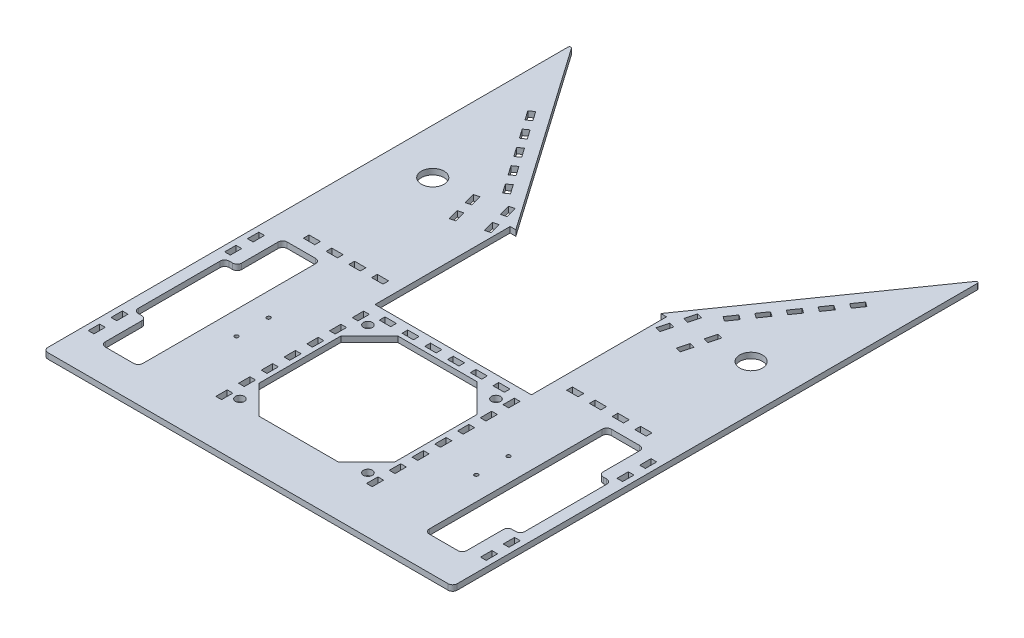
SolidWorks part; units mm, degrees
material "Acrylic (Medium-high impact)"
ref_plane "Front Plane" through (0, 0, 0) normal (0, 0, 1) x (1, 0, 0)
ref_plane "Top Plane" through (0, 0, 0) normal (0, 1, 0) x (1, 0, 0)
ref_plane "Right Plane" through (0, 0, 0) normal (1, 0, 0) x (0, 0, -1)
sketch "Sketch1" plane through (0, 0, 0) normal (0, 1, 0) x (1, 0, 0)
  line L0 (0, 0) -> (0, 279.4)
  line L1 (0, 0) -> (228.6, 0) construction
  line L2 (228.6, 0) -> (228.6, 279.4)
  line L3 (228.6, 279.4) -> (157.975, 178.425)
  line L4 (157.975, 178.425) -> (157.975, 98.425) construction
  line L5 (157.975, 98.425) -> (70.625, 98.425)
  line L6 (70.625, 98.425) -> (70.625, 178.425) construction
  line L7 (70.625, 178.425) -> (0, 279.4)
  line L8 (70.625, 178.425) -> (0, 178.425) construction
  line L9 (157.975, 178.425) -> (228.6, 178.425) construction
  line L10 (70.625, 50.8) -> (157.975, 50.8) construction
  line L11 (114.3, -1000) -> (114.3, 49000) construction
  line L12 (194.31, 2.54) -> (215.265, 2.54)
  line L13 (194.31, 2.54) -> (194.31, 104.14)
  line L14 (194.31, 104.14) -> (215.265, 104.14)
  line L15 (222.25, 27.94) -> (222.25, 78.74)
  line L16 (34.29, 53.34) -> (6.35, 53.34) construction
  line L17 (13.335, 104.14) -> (13.335, 78.74)
  line L18 (13.335, 78.74) -> (6.35, 78.74)
  line L19 (13.335, 27.94) -> (6.35, 27.94)
  line L20 (154.8, 85.725) -> (154.8, 92.075)
  line L21 (70.625, 53.975) -> (73.8, 53.975)
  line L22 (70.625, 53.975) -> (70.625, 47.625)
  line L23 (70.625, 47.625) -> (73.8, 47.625)
  line L24 (73.8, 53.975) -> (73.8, 47.625)
  line L25 (70.625, 41.275) -> (73.8, 41.275)
  line L26 (70.625, 41.275) -> (70.625, 34.925)
  line L27 (70.625, 34.925) -> (73.8, 34.925)
  line L28 (73.8, 41.275) -> (73.8, 34.925)
  line L29 (70.625, 28.575) -> (73.8, 28.575)
  line L30 (70.625, 28.575) -> (70.625, 22.225)
  line L31 (70.625, 22.225) -> (73.8, 22.225)
  line L32 (73.8, 28.575) -> (73.8, 22.225)
  line L33 (70.625, 15.875) -> (73.8, 15.875)
  line L34 (70.625, 15.875) -> (70.625, 9.525)
  line L35 (70.625, 9.525) -> (73.8, 9.525)
  line L36 (73.8, 15.875) -> (73.8, 9.525)
  line L37 (70.625, 60.325) -> (73.8, 60.325)
  line L38 (70.625, 60.325) -> (70.625, 66.675)
  line L39 (70.625, 66.675) -> (73.8, 66.675)
  line L40 (73.8, 60.325) -> (73.8, 66.675)
  line L41 (70.625, 73.025) -> (73.8, 73.025)
  line L42 (70.625, 73.025) -> (70.625, 79.375)
  line L43 (70.625, 79.375) -> (73.8, 79.375)
  line L44 (73.8, 73.025) -> (73.8, 79.375)
  line L45 (70.625, 85.725) -> (73.8, 85.725)
  line L46 (70.625, 85.725) -> (70.625, 92.075)
  line L47 (70.625, 92.075) -> (73.8, 92.075)
  line L48 (73.8, 85.725) -> (73.8, 92.075)
  line L49 (157.975, 92.075) -> (154.8, 92.075)
  line L50 (157.975, 85.725) -> (157.975, 92.075)
  line L51 (157.975, 85.725) -> (154.8, 85.725)
  line L52 (154.8, 73.025) -> (154.8, 79.375)
  line L53 (157.975, 79.375) -> (154.8, 79.375)
  line L54 (157.975, 73.025) -> (157.975, 79.375)
  line L55 (157.975, 73.025) -> (154.8, 73.025)
  line L56 (154.8, 60.325) -> (154.8, 66.675)
  line L57 (157.975, 66.675) -> (154.8, 66.675)
  line L58 (157.975, 60.325) -> (157.975, 66.675)
  line L59 (157.975, 60.325) -> (154.8, 60.325)
  line L60 (154.8, 15.875) -> (154.8, 9.525)
  line L61 (157.975, 9.525) -> (154.8, 9.525)
  line L62 (157.975, 15.875) -> (157.975, 9.525)
  line L63 (157.975, 15.875) -> (154.8, 15.875)
  line L64 (154.8, 28.575) -> (154.8, 22.225)
  line L65 (157.975, 22.225) -> (154.8, 22.225)
  line L66 (157.975, 28.575) -> (157.975, 22.225)
  line L67 (157.975, 28.575) -> (154.8, 28.575)
  line L68 (154.8, 41.275) -> (154.8, 34.925)
  line L69 (157.975, 34.925) -> (154.8, 34.925)
  line L70 (157.975, 41.275) -> (157.975, 34.925)
  line L71 (157.975, 41.275) -> (154.8, 41.275)
  line L72 (154.8, 53.975) -> (154.8, 47.625)
  line L73 (157.975, 47.625) -> (154.8, 47.625)
  line L74 (157.975, 53.975) -> (157.975, 47.625)
  line L75 (157.975, 53.975) -> (154.8, 53.975)
  line L76 (92.075, 9.525) -> (98.425, 9.525) construction
  line L77 (79.375, 9.525) -> (85.725, 9.525) construction
  line L78 (79.375, 9.525) -> (79.375, 6.35) construction
  line L79 (79.375, 6.35) -> (85.725, 6.35) construction
  line L80 (85.725, 9.525) -> (85.725, 6.35) construction
  line L81 (92.075, 9.525) -> (92.075, 6.35) construction
  line L82 (92.075, 6.35) -> (98.425, 6.35) construction
  line L83 (98.425, 9.525) -> (98.425, 6.35) construction
  line L84 (104.775, 9.525) -> (111.125, 9.525) construction
  line L85 (104.775, 9.525) -> (104.775, 6.35) construction
  line L86 (104.775, 6.35) -> (111.125, 6.35) construction
  line L87 (111.125, 9.525) -> (111.125, 6.35) construction
  line L88 (117.475, 9.525) -> (117.475, 6.35) construction
  line L89 (123.825, 6.35) -> (117.475, 6.35) construction
  line L90 (123.825, 9.525) -> (123.825, 6.35) construction
  line L91 (123.825, 9.525) -> (117.475, 9.525) construction
  line L92 (130.175, 9.525) -> (130.175, 6.35) construction
  line L93 (136.525, 6.35) -> (130.175, 6.35) construction
  line L94 (136.525, 9.525) -> (136.525, 6.35) construction
  line L95 (142.875, 9.525) -> (142.875, 6.35) construction
  line L96 (149.225, 6.35) -> (142.875, 6.35) construction
  line L97 (149.225, 9.525) -> (149.225, 6.35) construction
  line L98 (149.225, 9.525) -> (142.875, 9.525) construction
  line L99 (136.525, 9.525) -> (130.175, 9.525) construction
  line L100 (136.525, 92.075) -> (130.175, 92.075)
  line L101 (149.225, 92.075) -> (142.875, 92.075)
  line L102 (149.225, 92.075) -> (149.225, 95.25)
  line L103 (149.225, 95.25) -> (142.875, 95.25)
  line L104 (142.875, 92.075) -> (142.875, 95.25)
  line L105 (136.525, 92.075) -> (136.525, 95.25)
  line L106 (136.525, 95.25) -> (130.175, 95.25)
  line L107 (130.175, 92.075) -> (130.175, 95.25)
  line L108 (123.825, 92.075) -> (117.475, 92.075)
  line L109 (123.825, 92.075) -> (123.825, 95.25)
  line L110 (123.825, 95.25) -> (117.475, 95.25)
  line L111 (117.475, 92.075) -> (117.475, 95.25)
  line L112 (111.125, 92.075) -> (111.125, 95.25)
  line L113 (104.775, 95.25) -> (111.125, 95.25)
  line L114 (104.775, 92.075) -> (104.775, 95.25)
  line L115 (104.775, 92.075) -> (111.125, 92.075)
  line L116 (98.425, 92.075) -> (98.425, 95.25)
  line L117 (92.075, 95.25) -> (98.425, 95.25)
  line L118 (92.075, 92.075) -> (92.075, 95.25)
  line L119 (85.725, 92.075) -> (85.725, 95.25)
  line L120 (79.375, 95.25) -> (85.725, 95.25)
  line L121 (79.375, 92.075) -> (79.375, 95.25)
  line L122 (79.375, 92.075) -> (85.725, 92.075)
  line L123 (92.075, 92.075) -> (98.425, 92.075)
  line L124 (194.31, 53.34) -> (222.25, 53.34) construction
  line L125 (215.265, 2.54) -> (215.265, 27.94)
  line L126 (215.265, 27.94) -> (222.25, 27.94)
  line L127 (215.265, 78.74) -> (222.25, 78.74)
  line L128 (215.265, 104.14) -> (215.265, 78.74)
  line L129 (13.335, 2.54) -> (13.335, 27.94)
  line L130 (6.35, 27.94) -> (6.35, 78.74)
  line L131 (34.29, 104.14) -> (13.335, 104.14)
  line L132 (34.29, 2.54) -> (34.29, 104.14)
  line L133 (34.29, 2.54) -> (13.335, 2.54)
  line L134 (225.425, 94.615) -> (225.425, 100.965)
  line L135 (222.25, 24.765) -> (225.425, 24.765)
  line L136 (222.25, 24.765) -> (222.25, 18.415)
  line L137 (222.25, 18.415) -> (225.425, 18.415)
  line L138 (225.425, 24.765) -> (225.425, 18.415)
  line L139 (222.25, 12.065) -> (225.425, 12.065)
  line L140 (222.25, 12.065) -> (222.25, 5.715)
  line L141 (222.25, 5.715) -> (225.425, 5.715)
  line L142 (225.425, 12.065) -> (225.425, 5.715)
  line L143 (222.25, 100.965) -> (225.425, 100.965)
  line L144 (222.25, 94.615) -> (222.25, 100.965)
  line L145 (222.25, 94.615) -> (225.425, 94.615)
  line L146 (225.425, 81.915) -> (225.425, 88.265)
  line L147 (222.25, 88.265) -> (225.425, 88.265)
  line L148 (222.25, 81.915) -> (222.25, 88.265)
  line L149 (222.25, 81.915) -> (225.425, 81.915)
  line L150 (6.35, 81.915) -> (3.175, 81.915)
  line L151 (6.35, 81.915) -> (6.35, 88.265)
  line L152 (6.35, 88.265) -> (3.175, 88.265)
  line L153 (3.175, 81.915) -> (3.175, 88.265)
  line L154 (6.35, 94.615) -> (3.175, 94.615)
  line L155 (6.35, 94.615) -> (6.35, 100.965)
  line L156 (6.35, 100.965) -> (3.175, 100.965)
  line L157 (3.175, 94.615) -> (3.175, 100.965)
  line L158 (3.175, 12.065) -> (3.175, 5.715)
  line L159 (6.35, 5.715) -> (3.175, 5.715)
  line L160 (6.35, 12.065) -> (6.35, 5.715)
  line L161 (6.35, 12.065) -> (3.175, 12.065)
  line L162 (3.175, 24.765) -> (3.175, 18.415)
  line L163 (6.35, 18.415) -> (3.175, 18.415)
  line L164 (6.35, 24.765) -> (6.35, 18.415)
  line L165 (6.35, 24.765) -> (3.175, 24.765)
  line L166 (173.659, 189.7697) -> (177.2985, 194.9733)
  line L167 (173.659, 189.7697) -> (176.2607, 187.95)
  line L168 (178.9875, 197.6665) -> (181.5892, 195.8467) construction
  line L169 (176.2607, 187.95) -> (179.9002, 193.1535)
  line L170 (177.2985, 194.9733) -> (179.9002, 193.1535)
  line L171 (180.9379, 200.1768) -> (183.5397, 198.357)
  line L172 (187.1792, 203.5605) -> (183.5397, 198.357)
  line L173 (184.5774, 205.3803) -> (187.1792, 203.5605)
  line L174 (184.5774, 205.3803) -> (180.9379, 200.1768)
  line L175 (182.627, 202.87) -> (185.2287, 201.0502) construction
  line L176 (186.2665, 208.0735) -> (188.8682, 206.2537) construction
  line L177 (29.4646, 226.1943) -> (33.1041, 220.9908)
  line L178 (188.2169, 210.5838) -> (191.8564, 215.7873)
  line L179 (188.2169, 210.5838) -> (190.8187, 208.7641)
  line L180 (190.8187, 208.7641) -> (194.4582, 213.9676)
  line L181 (191.8564, 215.7873) -> (194.4582, 213.9676)
  line L182 (195.4959, 220.9908) -> (198.0977, 219.1711)
  line L183 (201.7372, 224.3746) -> (198.0977, 219.1711)
  line L184 (199.1354, 226.1943) -> (201.7372, 224.3746)
  line L185 (199.1354, 226.1943) -> (195.4959, 220.9908)
  line L186 (29.4646, 226.1943) -> (26.8628, 224.3746)
  line L187 (26.8628, 224.3746) -> (30.5023, 219.1711)
  line L188 (33.1041, 220.9908) -> (30.5023, 219.1711)
  line L189 (36.7436, 215.7873) -> (34.1418, 213.9676)
  line L190 (37.7813, 208.7641) -> (34.1418, 213.9676)
  line L191 (40.3831, 210.5838) -> (37.7813, 208.7641)
  line L192 (40.3831, 210.5838) -> (36.7436, 215.7873)
  line L193 (47.6621, 200.1768) -> (45.0603, 198.357)
  line L194 (44.0226, 205.3803) -> (47.6621, 200.1768)
  line L195 (44.0226, 205.3803) -> (41.4208, 203.5605)
  line L196 (41.4208, 203.5605) -> (45.0603, 198.357)
  line L197 (51.3015, 194.9733) -> (48.6998, 193.1535)
  line L198 (52.3393, 187.95) -> (48.6998, 193.1535)
  line L199 (54.941, 189.7697) -> (52.3393, 187.95)
  line L200 (54.941, 189.7697) -> (51.3015, 194.9733)
  line L201 (197.1849, 223.684) -> (199.7867, 221.8643) construction
  line L202 (202.7749, 231.3979) -> (205.3767, 229.5781)
  line L203 (209.0162, 234.7816) -> (205.3767, 229.5781)
  line L204 (206.4144, 236.6014) -> (202.7749, 231.3979)
  line L205 (206.4144, 236.6014) -> (209.0162, 234.7816)
  line L206 (22.1856, 236.6014) -> (19.5838, 234.7816)
  line L207 (22.1856, 236.6014) -> (25.8251, 231.3979)
  line L208 (19.5838, 234.7816) -> (23.2233, 229.5781)
  line L209 (25.8251, 231.3979) -> (23.2233, 229.5781)
  line L210 (76.3, 73.6934) -> (76.3, 27.9066)
  line L211 (76.3, 73.6934) -> (92.1816, 89.575)
  line L212 (92.1816, 89.575) -> (136.4184, 89.575)
  line L213 (92.1816, 12.025) -> (136.4184, 12.025)
  line L214 (76.3, 27.9066) -> (92.1816, 12.025)
  line L215 (152.3, 73.6934) -> (136.4184, 89.575)
  line L216 (152.3, 73.6934) -> (152.3, 27.9066)
  line L217 (152.3, 27.9066) -> (136.4184, 12.025)
  line L218 (165.2868, 183.9813) -> (163.6433, 177.8476)
  line L219 (165.2868, 183.9813) -> (168.1818, 183.2055)
  line L220 (163.6433, 177.8476) -> (166.5383, 177.0719)
  line L221 (168.1818, 183.2055) -> (166.5383, 177.0719)
  line L222 (180.7926, 179.8265) -> (179.1491, 173.6929)
  line L223 (180.7926, 179.8265) -> (183.6876, 179.0507)
  line L224 (179.1491, 173.6929) -> (182.0441, 172.9171)
  line L225 (183.6876, 179.0507) -> (182.0441, 172.9171)
  line L226 (161.9998, 171.714) -> (160.3563, 165.5804)
  line L227 (161.9998, 171.714) -> (164.8948, 170.9383)
  line L228 (160.3563, 165.5804) -> (163.2513, 164.8046)
  line L229 (164.8948, 170.9383) -> (163.2513, 164.8046)
  line L230 (177.5056, 167.5592) -> (175.8621, 161.4256)
  line L231 (177.5056, 167.5592) -> (180.4006, 166.7835)
  line L232 (175.8621, 161.4256) -> (178.7571, 160.6499)
  line L233 (180.4006, 166.7835) -> (178.7571, 160.6499)
  line L234 (48.1994, 166.7835) -> (49.8429, 160.6499)
  line L235 (52.7379, 161.4256) -> (49.8429, 160.6499)
  line L236 (51.0944, 167.5592) -> (48.1994, 166.7835)
  line L237 (51.0944, 167.5592) -> (52.7379, 161.4256)
  line L238 (63.7052, 170.9383) -> (65.3487, 164.8046)
  line L239 (68.2437, 165.5804) -> (65.3487, 164.8046)
  line L240 (66.6002, 171.714) -> (63.7052, 170.9383)
  line L241 (66.6002, 171.714) -> (68.2437, 165.5804)
  line L242 (44.9124, 179.0507) -> (46.5559, 172.9171)
  line L243 (49.4509, 173.6929) -> (46.5559, 172.9171)
  line L244 (47.8074, 179.8265) -> (44.9124, 179.0507)
  line L245 (47.8074, 179.8265) -> (49.4509, 173.6929)
  line L246 (60.4182, 183.2055) -> (62.0617, 177.0719)
  line L247 (64.9567, 177.8476) -> (62.0617, 177.0719)
  line L248 (63.3132, 183.9812) -> (60.4182, 183.2055)
  line L249 (63.3132, 183.9812) -> (64.9567, 177.8476)
  line L250 (43.955, 110.49) -> (50.305, 110.49)
  line L251 (56.655, 113.665) -> (63.005, 113.665)
  line L252 (56.655, 113.665) -> (56.655, 110.49)
  line L253 (56.655, 110.49) -> (63.005, 110.49)
  line L254 (63.005, 113.665) -> (63.005, 110.49)
  line L255 (50.305, 113.665) -> (50.305, 110.49)
  line L256 (43.955, 113.665) -> (50.305, 113.665)
  line L257 (43.955, 113.665) -> (43.955, 110.49)
  line L258 (31.255, 110.49) -> (37.605, 110.49)
  line L259 (37.605, 113.665) -> (37.605, 110.49)
  line L260 (31.255, 113.665) -> (37.605, 113.665)
  line L261 (31.255, 113.665) -> (31.255, 110.49)
  line L262 (18.555, 110.49) -> (24.905, 110.49)
  line L263 (24.905, 113.665) -> (24.905, 110.49)
  line L264 (18.555, 113.665) -> (24.905, 113.665)
  line L265 (18.555, 113.665) -> (18.555, 110.49)
  line L266 (0, 0) -> (0, -16.1925)
  line L267 (0, -16.1925) -> (228.6, -16.1925)
  line L268 (228.6, -16.1925) -> (228.6, 0)
  line L269 (70.625, 178.425) -> (73.8, 173.8856)
  line L270 (73.8, 173.8856) -> (70.625, 173.8856)
  line L271 (70.625, 173.8856) -> (70.625, 98.425)
  line L272 (157.975, 178.425) -> (154.8, 173.8856)
  line L273 (154.8, 173.8856) -> (157.975, 173.8856)
  line L274 (210.045, 113.665) -> (210.045, 110.49)
  line L275 (210.045, 113.665) -> (203.695, 113.665)
  line L276 (203.695, 113.665) -> (203.695, 110.49)
  line L277 (210.045, 110.49) -> (203.695, 110.49)
  line L278 (197.345, 113.665) -> (197.345, 110.49)
  line L279 (197.345, 113.665) -> (190.995, 113.665)
  line L280 (190.995, 113.665) -> (190.995, 110.49)
  line L281 (197.345, 110.49) -> (190.995, 110.49)
  line L282 (184.645, 113.665) -> (184.645, 110.49)
  line L283 (184.645, 113.665) -> (178.295, 113.665)
  line L284 (178.295, 113.665) -> (178.295, 110.49)
  line L285 (165.595, 113.665) -> (165.595, 110.49)
  line L286 (171.945, 110.49) -> (165.595, 110.49)
  line L287 (171.945, 113.665) -> (171.945, 110.49)
  line L288 (171.945, 113.665) -> (165.595, 113.665)
  line L289 (184.645, 110.49) -> (178.295, 110.49)
  line L290 (157.975, 173.8856) -> (157.975, 98.425)
  line L306 (5.855, 110.49) -> (12.205, 110.49) [skipped]
  line L307 (12.205, 113.665) -> (12.205, 110.49) [skipped]
  line L308 (5.855, 113.665) -> (12.205, 113.665) [skipped]
  line L309 (5.855, 113.665) -> (5.855, 110.49) [skipped]
  circle A0 centre (181.26, 44.34) radius 1.0541
  circle A1 centre (181.26, 62.34) radius 1.0541
  circle A2 centre (47.34, 62.34) radius 1.0541
  circle A3 centre (47.34, 44.34) radius 1.0541
  circle A4 centre (78.55, 15.05) radius 2.5
  circle A5 centre (78.55, 86.55) radius 2.5
  circle A6 centre (150.05, 15.05) radius 2.5
  circle A7 centre (150.05, 86.55) radius 2.5
  circle A8 centre (203.2, 175.885) radius 6.35
  circle A9 centre (25.4, 175.885) radius 6.35
  point P17 (194.31, 53.34)
  point P21 (114.3, 0)
  point P244 (76.3, 50.8)
  point P246 (114.3, 89.575)
  point P248 (114.3, 12.025)
  dimension "D27" = 18
  dimension "D26" = 2.1082
  dimension "D29" = 13.05
  dimension "D41" = 5
  dimension "D59" = 12.7
  dimension "D1" = 279.4
  dimension "D2" = 98.425
  dimension "D3" = 87.35
  dimension "D4" = 80
  dimension "D5" = 228.6
  dimension "D6" = 101.6
  dimension "D7" = 27.94
  dimension "D8" = 6.35
  dimension "D9" = 6.35
  dimension "D10" = 3.175
  dimension "D11" = 6.35
  dimension "D12" = 6.35
  dimension "D13" = 6.35
  dimension "D14" = 40.5
  dimension "D15" = 9.525
  dimension "D16" = 6.35
  dimension "D17" = 6.35
  dimension "D18" = 6.35
  dimension "D19" = 6.35
  dimension "D20" = 3.175
  dimension "D21" = 3.175
  dimension "D22" = 6.35
  dimension "D23" = 6.35
  dimension "D24" = 9.525
  dimension "D25" = 2.54
  dimension "D28" = 9
  dimension "D30" = 25.4
  dimension "D31" = 6.985
  dimension "D32" = 6.35
  dimension "D33" = 3.175
  dimension "D34" = 3.175
  dimension "D35" = 6.35
  dimension "D36" = 6.35
  dimension "D37" = 9.525
  dimension "D38" = 3.175
  dimension "D39" = 6.35
  dimension "D40" = 3.175
  dimension "D42" = 71.5
  dimension "D43" = 35.75
  dimension "D44" = 71.5
  dimension "D45" = 2.5
  dimension "D46" = 2.5
  dimension "D47" = 45
  dimension "D48" = 7.5
  dimension "D49" = 2.9972
  dimension "D50" = 6.35
  dimension "D51" = 15
  dimension "D52" = 6.35
  dimension "D53" = 19.05
  dimension "D54" = 2.3813
  dimension "D55" = 6.35
  dimension "D57" = 5
  dimension "D56" = 7.62
  dimension "D58" = 6.35
  dimension "D60" = 25.4
  dimension "D61" = 2.54
  dimension "D62" = 5.5562
  dimension "D63" = 16.1925
  dimension "D64" = 3.175
extrude "Boss-Extrude1" add sketch "Sketch1" along normal blind 3.175
fillet "Fillet1" radius 2.54 18 edges at (222.25, 1.5875, -27.94) (215.265, 1.5875, -27.94) (215.265, 1.5875, -2.54) (194.31, 1.5875, -2.54) (222.25, 1.5875, -78.74) (215.265, 1.5875, -78.74) (215.265, 1.5875, -104.14) (194.31, 1.5875, -104.14) (6.35, 1.5875, -78.74) (34.29, 1.5875, -2.54) (13.335, 1.5875, -2.54) (13.335, 1.5875, -27.94) (6.35, 1.5875, -27.94) (34.29, 1.5875, -104.14) (13.335, 1.5875, -104.14) (13.335, 1.5875, -78.74) (228.6, 1.5875, 16.1925) (0, 1.5875, 16.1925)
fillet "Fillet3" radius 0.7937 2 edges at (228.6, 1.5875, -279.4) (0, 1.5875, -279.4)
